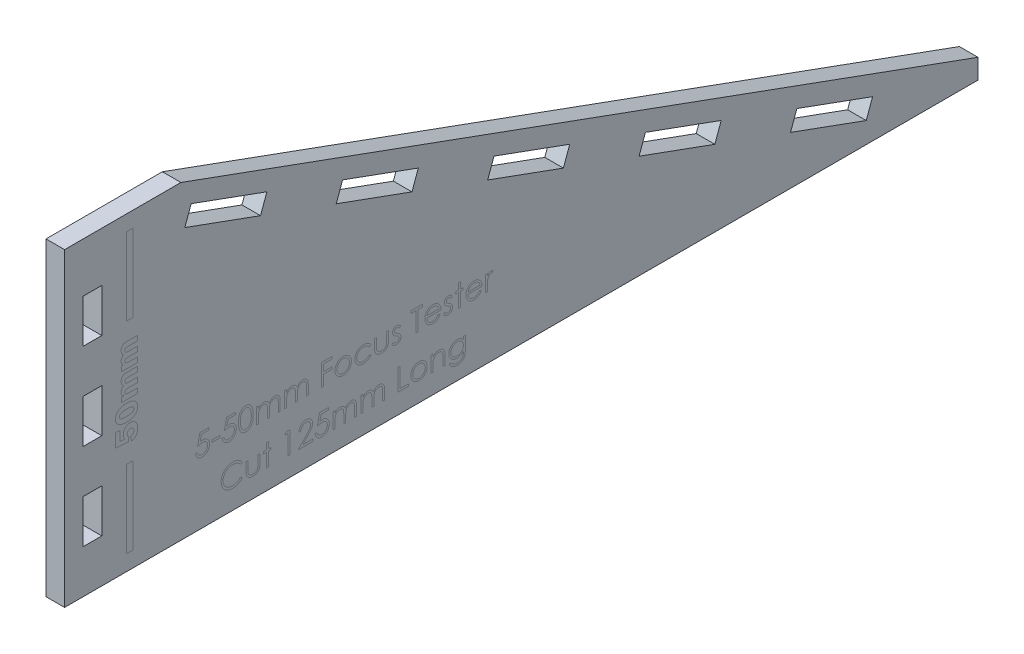
SolidWorks part; units mm, degrees
ref_plane "Front Plane" through (0, 0, 0) normal (0, 0, 1) x (1, 0, 0)
ref_plane "Top Plane" through (0, 0, 0) normal (0, 1, 0) x (1, 0, 0)
ref_plane "Right Plane" through (0, 0, 0) normal (1, 0, 0) x (0, 0, -1)
sketch "Sketch1" plane through (0, 0, 0) normal (1, 0, 0) x (0, 0, -1)
  line L0 (0, 0) -> (0, 50) construction
  line L1 (0, 0) -> (137.3739, 0) construction
  line L2 (137.3739, 0) -> (0, 50) construction
  line L3 (136.3478, -2.8191) -> (-1.0261, 47.1809) construction
  line L4 (0, 50) -> (-10, 50)
  line L5 (-10, 50) -> (-10, 0)
  line L6 (-10, 0) -> (137.3739, 0)
  line L7 (137.3739, 0) -> (137.3739, 3.1925)
  line L8 (137.3739, 3.1925) -> (8.7714, 50)
  line L9 (8.7714, 50) -> (0, 50)
  line L10 (10.423, 46.2063) -> (9.3969, 43.3873)
  line L11 (9.3969, 43.3873) -> (21.6129, 38.941)
  line L12 (21.6129, 38.941) -> (22.639, 41.7601)
  line L13 (22.639, 41.7601) -> (10.423, 46.2063)
  line L14 (34.855, 37.3138) -> (33.8289, 34.4947)
  line L15 (33.8289, 34.4947) -> (46.0449, 30.0485)
  line L16 (46.0449, 30.0485) -> (47.071, 32.8676)
  line L17 (47.071, 32.8676) -> (34.855, 37.3138)
  line L18 (119.341, 3.3709) -> (120.367, 6.19)
  line L19 (120.367, 6.19) -> (108.151, 10.6362)
  line L20 (108.151, 10.6362) -> (107.125, 7.8172)
  line L21 (107.125, 7.8172) -> (119.341, 3.3709)
  line L22 (95.935, 15.0825) -> (94.909, 12.2634)
  line L23 (94.909, 12.2634) -> (82.693, 16.7097)
  line L24 (82.693, 16.7097) -> (83.719, 19.5288)
  line L25 (83.719, 19.5288) -> (95.935, 15.0825)
  line L26 (59.287, 28.4213) -> (58.2609, 25.6022)
  line L27 (58.2609, 25.6022) -> (70.4769, 21.156)
  line L28 (70.4769, 21.156) -> (71.503, 23.975)
  line L29 (71.503, 23.975) -> (59.287, 28.4213)
  line L30 (9.3969, 43.3873) -> (0, 46.8075) construction
  line L31 (119.341, 3.3709) -> (128.6025, 0) construction
  line L32 (107.125, 7.8172) -> (94.909, 12.2634) construction
  line L33 (82.693, 16.7097) -> (70.4769, 21.156) construction
  line L34 (58.2609, 25.6022) -> (46.0449, 30.0485) construction
  line L35 (33.8289, 34.4947) -> (21.6129, 38.941) construction
  line L36 (-7, 50) -> (-7, 0) construction
  line L37 (-4, 50) -> (-4, 0) construction
  line L38 (-7, 7) -> (-7, 0) construction
  line L39 (-7, 42) -> (-4, 42)
  line L40 (-7, 42) -> (-7, 35)
  line L41 (-7, 35) -> (-4, 35)
  line L42 (-4, 42) -> (-4, 35)
  line L43 (-7, 28) -> (-4, 28)
  line L44 (-7, 28) -> (-7, 21)
  line L45 (-7, 21) -> (-4, 21)
  line L46 (-4, 28) -> (-4, 21)
  line L47 (-7, 14) -> (-4, 14)
  line L48 (-7, 14) -> (-7, 7)
  line L49 (-7, 7) -> (-4, 7)
  line L50 (-4, 14) -> (-4, 7)
  line L51 (-7, 21) -> (-7, 14) construction
  line L52 (-7, 35) -> (-7, 28) construction
  line L53 (123.6365, 5) -> (123.6365, 0) construction
  line L54 (0, 46.8075) -> (1.0261, 49.6265) construction
  dimension "D1" = 50
  dimension "D2" = 70
  dimension "D4" = 3
  dimension "D5" = 10
  dimension "D6" = 13
  dimension "D7" = 136.8559
  dimension "D8" = 10
  dimension "D11" = 7
  dimension "D12" = 5
  dimension "D13" = 123.6365
  dimension "D14" = 7
  dimension "D15" = 0.3735
  dimension "D3" = 3
  dimension "D9" = 3
  dimension "D10" = 3
extrude "Boss-Extrude1" add sketch "Sketch1" along normal blind 3
sketch "Sketch2" plane through (3, 0, 0) normal (1, 0, 0) x (0, 0, -1)
  line L0 (8.7714, 50) -> (-10, 50) construction
  line L1 (0, 47.5) -> (1, 47.5)
  line L2 (0, 47.5) -> (0, 35)
  line L3 (0, 35) -> (1, 35)
  line L4 (1, 47.5) -> (1, 35)
  line L5 (-10, 25) -> (1, 25) construction
  line L6 (-10, 50) -> (-10, 0) construction
  line L7 (1, 2.5) -> (1, 15)
  line L8 (0, 15) -> (1, 15)
  line L9 (0, 2.5) -> (0, 15)
  line L10 (0, 2.5) -> (1, 2.5)
  line L11 (1.75, 50) -> (1.75, 0) construction
  line L12 (-10, 0) -> (137.3739, 0) construction
  line L13 (10, 10) -> (60, 10) construction
  text T0 "50mm" font "Franklin Gothic Demi" height 3.5
  text T1 "5-50mm Focus Tester\r\nCut 125mm Long"
  dimension "D1" = 12.5
  dimension "D2" = 1
  dimension "D3" = 2.5
  dimension "D4" = 10
  dimension "D5" = 11.75
  dimension "D6" = 20
  dimension "D7" = 50
  dimension "D8" = 10
split line "Split Line1"
